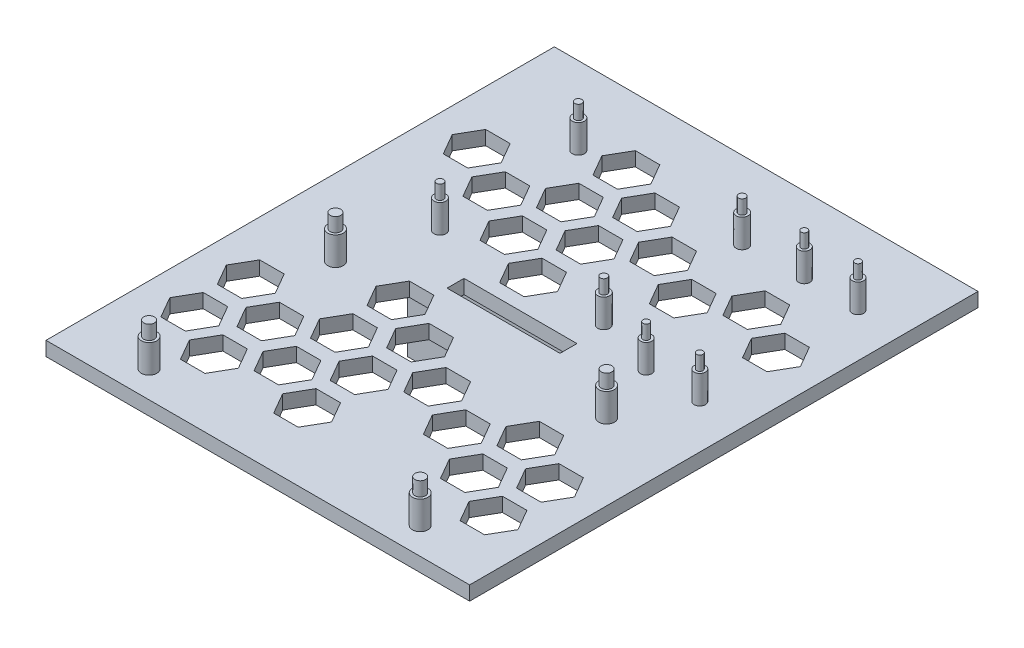
SolidWorks part; units mm, degrees
ref_plane "Front" through (0, 0, 0) normal (0, 0, 1) x (1, 0, 0)
ref_plane "Top" through (0, 0, 0) normal (0, 1, 0) x (1, 0, 0)
ref_plane "Right" through (0, 0, 0) normal (1, 0, 0) x (0, 0, -1)
sketch "Esquisse1" plane through (0, 0, 0) normal (0, 1, 0) x (1, 0, 0)
  line L1 (-31, 6) -> (31, 6)
  line L2 (-31, 6) -> (-31, -6)
  line L3 (-31, -6) -> (31, -6)
  line L4 (31, 6) -> (31, -6)
  line L5 (-31, 6) -> (31, -6) construction
  line L6 (-31, -6) -> (31, 6) construction
  line L7 (-29, 4) -> (29, 4)
  line L8 (-29, 4) -> (-29, -4)
  line L9 (-29, -4) -> (29, -4)
  line L10 (29, 4) -> (29, -4)
  line L11 (-29, 4) -> (29, -4) construction
  line L12 (-29, -4) -> (29, 4) construction
  point P0 (0, 0)
  point P6 (0, 0)
  dimension "D1" = 8
  dimension "D2" = 12
  dimension "D3" = 62
  dimension "D4" = 58
extrude "Boss.-Extru.1" add sketch "Esquisse1" along normal blind 20
sketch "Esquisse2" plane through (0, 0, 6) normal (0, 0, 1) x (1, 0, 0)
  line L0 (-31, 20) -> (31, 20) construction
  line L1 (31, 20) -> (31, 0) construction
  circle A0 centre (0, 8) radius 3.175
  dimension "D1" = 6.35
  dimension "D2" = 12
  dimension "D3" = 31
extrude "Enlèv. mat.-Extru.1" cut sketch "Esquisse2" against normal through all
sketch "Esquisse3" plane through (0, 20, 0) normal (0, 1, 0) x (1, 0, 0)
  line L1 (-75, 90) -> (75, 90)
  line L2 (-75, 90) -> (-75, -90)
  line L3 (-75, -90) -> (75, -90)
  line L4 (75, 90) -> (75, -90)
  line L5 (-75, 90) -> (75, -90) construction
  line L6 (-75, -90) -> (75, 90) construction
  point P0 (0, 0)
  dimension "D1" = 180
  dimension "D2" = 150
extrude "Boss.-Extru.2" add sketch "Esquisse3" along normal blind 5
sketch "Esquisse4" plane through (0, 25, 0) normal (0, 1, 0) x (1, 0, 0)
  line L0 (75, -90) -> (75, 90) construction
  line L1 (-52.5, -85) -> (52.5, -85) construction
  line L2 (-52.5, -85) -> (-52.5, -10) construction
  line L3 (-52.5, -10) -> (52.5, -10) construction
  line L4 (52.5, -85) -> (52.5, -10) construction
  line L5 (-52.5, -85) -> (52.5, -10) construction
  line L6 (-52.5, -10) -> (52.5, -85) construction
  line L7 (-75, -90) -> (75, -90) construction
  line L9 (-61.5, 10) -> (22.5, 10) construction
  line L10 (-61.5, 10) -> (-61.5, 66) construction
  line L11 (-61.5, 66) -> (22.5, 66) construction
  line L12 (22.5, 10) -> (22.5, 66) construction
  line L13 (-61.5, 10) -> (22.5, 66) construction
  line L14 (-61.5, 66) -> (22.5, 10) construction
  line L15 (37.5, 4) -> (62.5, 4) construction
  line L16 (37.5, 4) -> (37.5, 66) construction
  line L17 (37.5, 66) -> (62.5, 66) construction
  line L18 (62.5, 4) -> (62.5, 66) construction
  line L19 (37.5, 4) -> (62.5, 66) construction
  line L20 (37.5, 66) -> (62.5, 4) construction
  line L21 (75, 90) -> (-75, 90) construction
  point P4 (0, -47.5)
  point P10 (0, -90)
  point P15 (-19.5, 38)
  point P21 (50, 35)
  point P22 (75, 0)
  point P24 (0, 90)
  dimension "D1" = 75
  dimension "D2" = 105
  dimension "D3" = 10
  dimension "D4" = 56
  dimension "D5" = 84
  dimension "D6" = 15
  dimension "D7" = 62
  dimension "D8" = 25
  dimension "D9" = 22.5
  dimension "D10" = 10
sketch "Esquisse6" plane through (0, 20, 0) normal (0, -1, 0) x (-1, 0, 0)
  line L0 (-29, -4) -> (-29, 4) construction
  line L1 (20, 3) -> (-20, 3)
  line L2 (20, 3) -> (20, -3)
  line L3 (20, -3) -> (-20, -3)
  line L4 (-20, 3) -> (-20, -3)
  line L5 (20, 3) -> (-20, -3) construction
  line L6 (20, -3) -> (-20, 3) construction
  line L7 (29, -4) -> (-29, -4) construction
  point P4 (0, 0)
  point P8 (-29, 0)
  point P12 (0, -4)
  dimension "D1" = 6
  dimension "D2" = 40
extrude "Enlèv. mat.-Extru.3" cut sketch "Esquisse6" against normal up to next
sketch "Esquisse8" plane through (0, 25, 0) normal (0, 1, 0) x (1, 0, 0)
  line L0 (-61.5, 66) -> (22.5, 66) construction
  line L1 (22.5, 10) -> (22.5, 66) construction
  circle A0 centre (19, 62.5) radius 1.25
  circle A1 centre (19, 13.5) radius 1.25
  circle A2 centre (-39, 62.5) radius 1.25
  circle A3 centre (-39, 13.5) radius 1.25
  dimension "D1" = 2.5
  dimension "D4" = 2.5
  dimension "D6" = 2.5
  dimension "D8" = 2.5
  dimension "D2" = 3.5
  dimension "D3" = 3.5
  dimension "D5" = 49
  dimension "D7" = 58
sketch "Esquisse9" plane through (0, 25, 0) normal (0, 1, 0) x (1, 0, 0)
  line L0 (62.5, 4) -> (62.5, 66) construction
  line L1 (37.5, 66) -> (62.5, 66) construction
  circle A0 centre (59.5, 63) radius 1.125
  circle A1 centre (40.5, 63) radius 1.125
  circle A2 centre (59.5, 7) radius 1.125
  circle A3 centre (40.5, 7) radius 1.125
  dimension "D1" = 2.25
  dimension "D4" = 2.25
  dimension "D6" = 2.25
  dimension "D8" = 2.25
  dimension "D2" = 3
  dimension "D3" = 3
  dimension "D5" = 19
  dimension "D7" = 56
sketch "Esquisse10" plane through (0, 25, 0) normal (0, 1, 0) x (1, 0, 0)
  line L0 (-52.5, -10) -> (52.5, -10) construction
  line L1 (-52.5, -85) -> (-52.5, -10) construction
  circle A0 centre (-48, -14.5) radius 1.875
  circle A1 centre (48, -14.5) radius 1.875
  circle A2 centre (-48, -80.5) radius 1.875
  circle A3 centre (48, -80.5) radius 1.875
  dimension "D1" = 3.75
  dimension "D4" = 3.75
  dimension "D6" = 3.75
  dimension "D8" = 3.75
  dimension "D2" = 4.5
  dimension "D3" = 4.5
  dimension "D5" = 96
  dimension "D7" = 66
sketch "Esquisse11" plane through (0, 25, 0) normal (0, 1, 0) x (1, 0, 0)
  line L0 (-52.5, -10) -> (52.5, -10) construction
  line L1 (-52.5, -85) -> (-52.5, -10) construction
  circle A0 centre (-48, -14.5) radius 2.75
  circle A1 centre (-48, -80.5) radius 2.75
  circle A2 centre (48, -14.5) radius 2.75
  circle A3 centre (48, -80.5) radius 2.75
  dimension "D3" = 5.5
  dimension "D5" = 5.5
  dimension "D6" = 96
  dimension "D7" = 5.5
  dimension "D8" = 5.5
  dimension "D1" = 4.5
  dimension "D2" = 4.5
  dimension "D4" = 66
sketch "Esquisse12" plane through (0, 25, 0) normal (0, 1, 0) x (1, 0, 0)
  line L0 (-61.5, 66) -> (22.5, 66) construction
  line L1 (22.5, 10) -> (22.5, 66) construction
  circle A0 centre (19, 62.5) radius 2.125
  circle A1 centre (19, 13.5) radius 2.125
  circle A2 centre (-39, 62.5) radius 2.125
  circle A3 centre (-39, 13.5) radius 2.125
  dimension "D3" = 4.25
  dimension "D5" = 4.25
  dimension "D7" = 4.25
  dimension "D8" = 4.25
  dimension "D1" = 3.5
  dimension "D2" = 3.5
  dimension "D4" = 49
  dimension "D6" = 58
sketch "Esquisse13" plane through (0, 25, 0) normal (0, 1, 0) x (1, 0, 0)
  line L0 (37.5, 4) -> (62.5, 4) construction
  line L1 (62.5, 4) -> (62.5, 66) construction
  circle A0 centre (59.5, 7) radius 2
  circle A1 centre (59.5, 63) radius 2
  circle A2 centre (40.5, 7) radius 2
  circle A3 centre (40.5, 63) radius 2
  dimension "D3" = 4
  dimension "D4" = 4
  dimension "D6" = 4
  dimension "D8" = 4
  dimension "D1" = 3
  dimension "D2" = 3
  dimension "D5" = 56
  dimension "D7" = 19
extrude "Boss.-Extru.3" add sketch "Esquisse11" along normal blind 10
extrude "Boss.-Extru.4" add sketch "Esquisse13" along normal blind 10
extrude "Boss.-Extru.5" add sketch "Esquisse12" along normal blind 10
extrude "Boss.-Extru.6" add sketch "Esquisse10" along normal blind 15
extrude "Boss.-Extru.7" add sketch "Esquisse9" along normal blind 15
extrude "Boss.-Extru.8" add sketch "Esquisse8" along normal blind 15
sketch "Esquisse14" plane through (0, 25, 0) normal (0, 1, 0) x (1, 0, 0)
  line L0 (-75, -90) -> (75, -90) construction
  line L1 (-53.1699, -62.5) -> (-48.8397, -55)
  line L2 (-48.8397, -55) -> (-53.1699, -47.5)
  line L3 (-53.1699, -47.5) -> (-61.8301, -47.5)
  line L4 (-61.8301, -47.5) -> (-66.1603, -55)
  line L5 (-66.1603, -55) -> (-61.8301, -62.5)
  line L6 (-61.8301, -62.5) -> (-53.1699, -62.5)
  line L7 (-75, 90) -> (-75, -90) construction
  line L9 (-36.7154, -72) -> (-32.3853, -64.5)
  line L10 (-32.3853, -64.5) -> (-36.7154, -57)
  line L11 (-36.7154, -57) -> (-45.3756, -57)
  line L12 (-45.3756, -57) -> (-49.7058, -64.5)
  line L13 (-49.7058, -64.5) -> (-45.3756, -72)
  line L14 (-45.3756, -72) -> (-36.7154, -72)
  line L15 (-48.8397, -55) -> (-45.3756, -57) construction
  circle A0 centre (-57.5, -55) radius 7.5 construction
  circle A1 centre (-41.0455, -64.5) radius 7.5 construction
  dimension "D1" = 15
  dimension "D4" = 15
  dimension "D2" = 35
  dimension "D3" = 17.5
  dimension "D5" = 4
extrude "Enlèv. mat.-Extru.4" cut sketch "Esquisse14" against normal through all
pattern_linear "Répétition linéaire1" count 7 spacing 20 along (0, 0, -1) count 4 spacing 33 along (1, 0, 0) skipping (0, 2), (2, 0), (2, 2), (2, 3), (3, 0), (3, 1), (3, 2), (3, 3), (4, 0), (4, 2), (4, 3), (6, 0), (6, 2), (6, 3) of "Enlèv. mat.-Extru.4"
